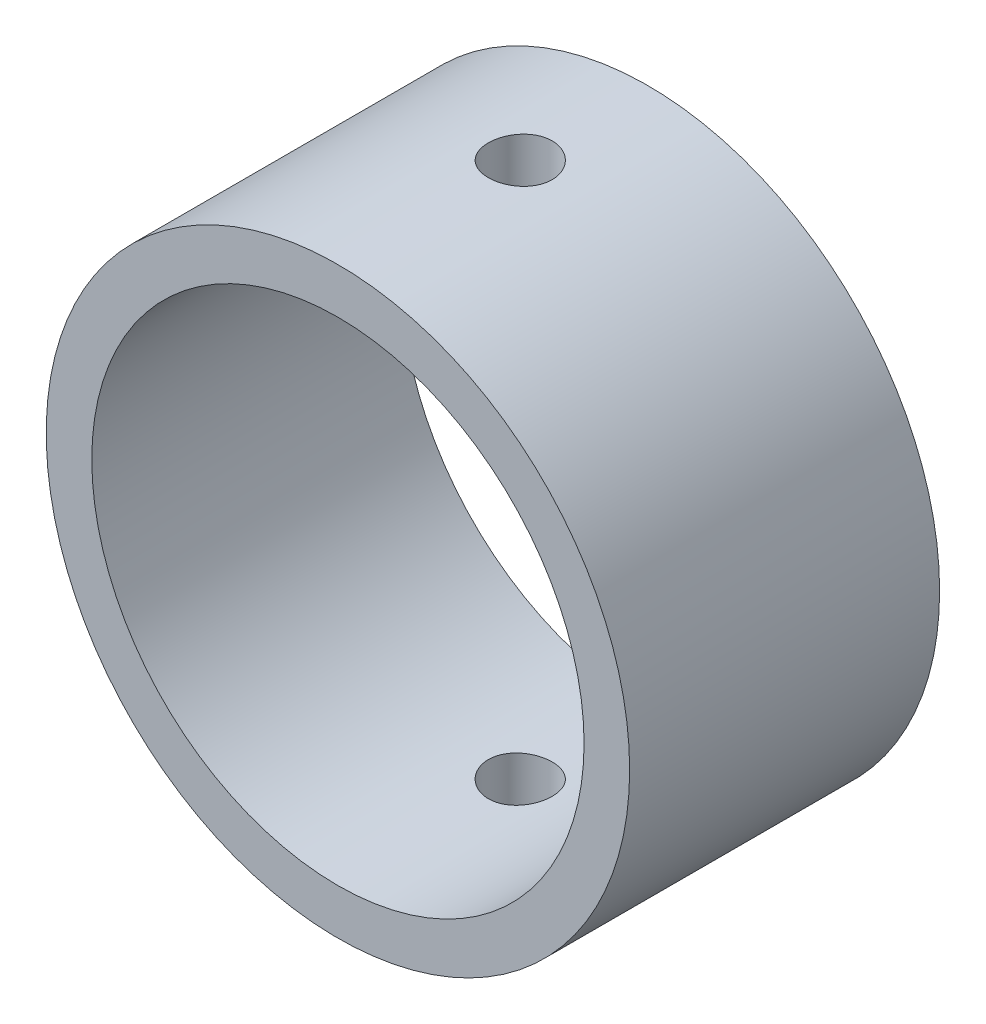
SolidWorks part; units mm, degrees
ref_plane "Front Plane" through (0, 0, 0) normal (0, 0, 1) x (1, 0, 0)
ref_plane "Top Plane" through (0, 0, 0) normal (0, 1, 0) x (1, 0, 0)
ref_plane "Right Plane" through (0, 0, 0) normal (1, 0, 0) x (0, 0, -1)
sketch "Sketch1" plane through (0, 0, 0) normal (0, 0, 1) x (1, 0, 0)
  circle A0 centre (0, 0) radius 16
  circle A1 centre (0, 0) radius 13.5
  dimension "D1" = 32
  dimension "D2" = 2.5
extrude "Boss-Extrude1" add sketch "Sketch1" along normal blind 17
ref_plane "Plane1" through (0, 16, 0) normal (0, 1, 0) x (1, 0, 0)
sketch "Sketch2" plane through (0, 16, 0) normal (0, 1, 0) x (1, 0, 0)
  line L0 (-24.2344, -7) -> (27.8633, -7) construction
  line L1 (16, 0) -> (-16, 0) construction
  circle A0 centre (0, -7) radius 1.75
  dimension "D1" = 7
extrude "Cut-Extrude1" cut sketch "Sketch2" against normal blind 35
